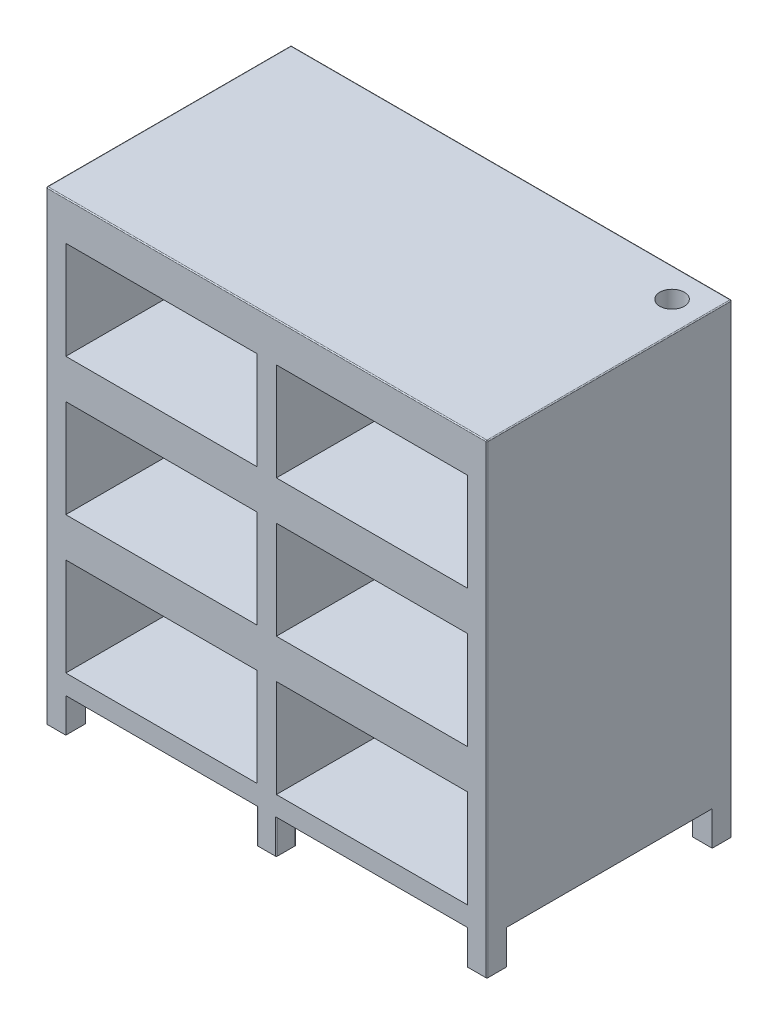
SolidWorks part; units mm, degrees
ref_plane "Front" through (0, 0, 0) normal (0, 0, 1) x (1, 0, 0)
ref_plane "Top" through (0, 0, 0) normal (0, 1, 0) x (1, 0, 0)
ref_plane "Right" through (0, 0, 0) normal (1, 0, 0) x (0, 0, -1)
sketch "Sketch1" plane through (0, 0, 0) normal (0, 1, 0) x (1, 0, 0)
  line L1 (51.2982, 0) -> (0, 0) construction
  dimension "D1" = 51.2982
sketch "Sketch2" plane through (0, 0, 0) normal (0, 1, 0) x (1, 0, 0)
  line L0 (0, 0) -> (0, 58.5054) construction
sketch "Sketch3" plane through (0, 0, 0) normal (0, 1, 0) x (1, 0, 0)
  line L0 (0, 0) -> (0, 58.5054) construction
  line L1 (520.7, 266.7) -> (571.5, 266.7)
  line L2 (520.7, 266.7) -> (520.7, 317.5)
  line L3 (520.7, 317.5) -> (571.5, 317.5)
  line L4 (571.5, 266.7) -> (571.5, 317.5)
  line L5 (520.7, 266.7) -> (571.5, 317.5) construction
  line L6 (520.7, 317.5) -> (571.5, 266.7) construction
  line L8 (51.2982, 0) -> (0, 0) construction
  point P4 (546.1, 292.1)
  dimension "D1" = 50.8
  dimension "D2" = 50.8
  dimension "D3" = 546.1
  dimension "D4" = 292.1
extrude "Boss-Extrude1" add sketch "Sketch3" along normal blind 88.9
sketch "Sketch4" plane through (0, 0, 0) normal (0, 1, 0) x (1, 0, 0)
  line L0 (51.2982, 0) -> (0, 0) construction
  line L1 (520.7, -266.7) -> (571.5, -266.7)
  line L2 (520.7, -266.7) -> (520.7, -317.5)
  line L3 (520.7, -317.5) -> (571.5, -317.5)
  line L4 (571.5, -266.7) -> (571.5, -317.5)
  line L5 (520.7, -266.7) -> (571.5, -317.5) construction
  line L6 (520.7, -317.5) -> (571.5, -266.7) construction
  line L7 (0, 0) -> (0, 58.5054) construction
  point P4 (546.1, -292.1)
  dimension "D1" = 50.8
  dimension "D2" = 50.8
  dimension "D3" = 292.1
  dimension "D4" = 546.1
extrude "Boss-Extrude2" add sketch "Sketch4" along normal blind 88.9 separate body
sketch "Sketch5" plane through (0, 0, 0) normal (0, 1, 0) x (1, 0, 0)
  line L0 (0, 0) -> (0, 58.5054) construction
  line L1 (-520.7, 266.7) -> (-571.5, 266.7)
  line L2 (-520.7, 266.7) -> (-520.7, 317.5)
  line L3 (-520.7, 317.5) -> (-571.5, 317.5)
  line L4 (-571.5, 266.7) -> (-571.5, 317.5)
  line L5 (-520.7, 266.7) -> (-571.5, 317.5) construction
  line L6 (-520.7, 317.5) -> (-571.5, 266.7) construction
  line L7 (51.2982, 0) -> (0, 0) construction
  point P4 (-546.1, 292.1)
  dimension "D1" = 50.8
  dimension "D2" = 50.8
  dimension "D3" = 546.1
  dimension "D4" = 292.1
extrude "Boss-Extrude3" add sketch "Sketch5" along normal blind 88.9 separate body
fillet "Fillet1" radius 0.1 4 edges at (571.5, 44.45, 317.5) (571.5, 44.45, 266.7) (520.7, 44.45, 266.7) (520.7, 44.45, 317.5)
fillet "Fillet2" radius 0.1 4 edges at (520.7, 44.45, -317.5) (520.7, 44.45, -266.7) (571.5, 44.45, -266.7) (571.5, 44.45, -317.5)
fillet "Fillet3" radius 0.1 4 edges at (-520.7, 44.45, -317.5) (-520.7, 44.45, -266.7) (-571.5, 44.45, -266.7) (-571.5, 44.45, -317.5)
sketch "Sketch6" plane through (0, 0, 0) normal (0, 1, 0) x (1, 0, 0)
  line L0 (0, 0) -> (0, 58.5054) construction
  line L1 (-520.7, -266.7) -> (-571.5, -266.7)
  line L2 (-520.7, -266.7) -> (-520.7, -317.5)
  line L3 (-520.7, -317.5) -> (-571.5, -317.5)
  line L4 (-571.5, -266.7) -> (-571.5, -317.5)
  line L5 (-520.7, -266.7) -> (-571.5, -317.5) construction
  line L6 (-520.7, -317.5) -> (-571.5, -266.7) construction
  line L7 (51.2982, 0) -> (0, 0) construction
  point P4 (-546.1, -292.1)
  dimension "D1" = 50.8
  dimension "D2" = 50.8
  dimension "D3" = 546.1
  dimension "D4" = 292.1
extrude "Boss-Extrude4" add sketch "Sketch6" along normal blind 88.9 separate body
fillet "Fillet4" radius 0.1 4 edges at (-571.5, 44.45, 266.7) (-520.7, 44.45, 266.7) (-520.7, 44.45, 317.5) (-571.5, 44.45, 317.5)
sketch "Sketch8" plane through (0, 0, 0) normal (0, 1, 0) x (1, 0, 0)
  line L0 (0, 58.5054) -> (0, 744.4795) construction
  line L2 (-25.4, 266.7) -> (25.4, 266.7)
  line L3 (-25.4, 266.7) -> (-25.4, 317.5)
  line L4 (-25.4, 317.5) -> (25.4, 317.5)
  line L5 (25.4, 266.7) -> (25.4, 317.5)
  line L6 (-25.4, 266.7) -> (25.4, 317.5) construction
  line L7 (-25.4, 317.5) -> (25.4, 266.7) construction
  point P4 (0, 292.1)
  dimension "D1" = 50.8
  dimension "D2" = 50.8
  dimension "D3" = 292.1
extrude "Boss-Extrude5" add sketch "Sketch8" along normal blind 88.9 separate body
sketch "Sketch9" plane through (0, 0, 0) normal (0, 1, 0) x (1, 0, 0)
  line L0 (0, 0) -> (0, -506.7029) construction
  line L2 (-25.4, -317.5) -> (25.4, -317.5)
  line L3 (-25.4, -317.5) -> (-25.4, -266.7)
  line L4 (-25.4, -266.7) -> (25.4, -266.7)
  line L5 (25.4, -317.5) -> (25.4, -266.7)
  line L6 (-25.4, -317.5) -> (25.4, -266.7) construction
  line L7 (-25.4, -266.7) -> (25.4, -317.5) construction
  point P3 (0, -292.1)
  dimension "D1" = 50.8
  dimension "D2" = 50.8
  dimension "D3" = 292.1
extrude "Boss-Extrude6" add sketch "Sketch9" along normal blind 88.9 separate body
fillet "Fillet5" radius 2.54 4 edges at (-25.4, 44.45, 266.7) (25.4, 44.45, 266.7) (25.4, 44.45, 317.5) (-25.4, 44.45, 317.5)
fillet "Fillet6" radius 2.54 4 edges at (25.4, 44.45, -317.5) (25.4, 44.45, -266.7) (-25.4, 44.45, -266.7) (-25.4, 44.45, -317.5)
ref_plane "Plane1" through (0, 88.9, 0) normal (0, 1, 0) x (1, 0, 0)
sketch "Sketch10" plane through (0, 88.9, 0) normal (0, 1, 0) x (1, 0, 0)
  line L1 (-571.5, -317.5) -> (571.5, -317.5)
  line L2 (-571.5, -317.5) -> (-571.5, 317.5)
  line L3 (-571.5, 317.5) -> (571.5, 317.5)
  line L4 (571.5, -317.5) -> (571.5, 317.5)
  line L5 (-571.5, -317.5) -> (571.5, 317.5) construction
  line L6 (-571.5, 317.5) -> (571.5, -317.5) construction
  point P0 (0, 0)
  dimension "D1" = 1143
  dimension "D2" = 635
extrude "Boss-Extrude7" add sketch "Sketch10" along normal blind 1117.6
sketch "Sketch11" plane through (0, 0, 317.5) normal (0, 0, 1) x (1, 0, 0)
  line L0 (-520.8, 88.9) -> (-22.86, 88.9) construction
  line L1 (-520.7, 139.7) -> (-25.4, 139.7)
  line L2 (-520.7, 139.7) -> (-520.7, 393.6096)
  line L3 (-520.7, 393.6096) -> (-25.4, 393.6096)
  line L4 (-25.4, 139.7) -> (-25.4, 393.6096)
  line L5 (-520.7, 139.7) -> (-25.4, 393.6096) construction
  line L6 (-520.7, 393.6096) -> (-25.4, 139.7) construction
  line L7 (-571.5, 1206.5) -> (-571.5, 88.9) construction
  line L8 (-25.4, 0) -> (-25.4, 88.9) construction
  point P4 (-273.05, 266.6548)
  dimension "D1" = 50.8
  dimension "D2" = 50.8
extrude "Cut-Extrude1" cut sketch "Sketch11" against normal blind 558.8
ref_plane "Plane2" through (-520.7, 139.7, 317.5) normal (0, 0, 1) x (1, 0, 0)
fillet "Fillet7" radius 2.54 7 edges at (-571.5, 1206.5, 0) (0, 1206.5, 317.5) (0, 1206.5, -317.5) (571.5, 1206.5, 0) (571.5, 647.7, -317.5) (571.5, 647.7, 317.5) (-571.5, 647.7, 317.5)
pattern_linear "LPattern1" count 3 spacing 355.6 along (0, 1, 0) count 2 spacing 546.1 along (1, 0, 0) of "Cut-Extrude1"
sketch "Sketch13" plane through (0, 1206.5, 0) normal (0, 1, 0) x (1, 0, 0)
  line L0 (-571.5, 317.5) -> (568.96, 317.5) construction
  line L1 (568.96, -314.96) -> (568.96, 314.96) construction
  circle A0 centre (492.76, 241.3) radius 31.75
  dimension "D1" = 76.2
  dimension "D2" = 63.5
  dimension "D3" = 76.2
extrude "Cut-Extrude2" cut sketch "Sketch13" against normal blind 970.026
